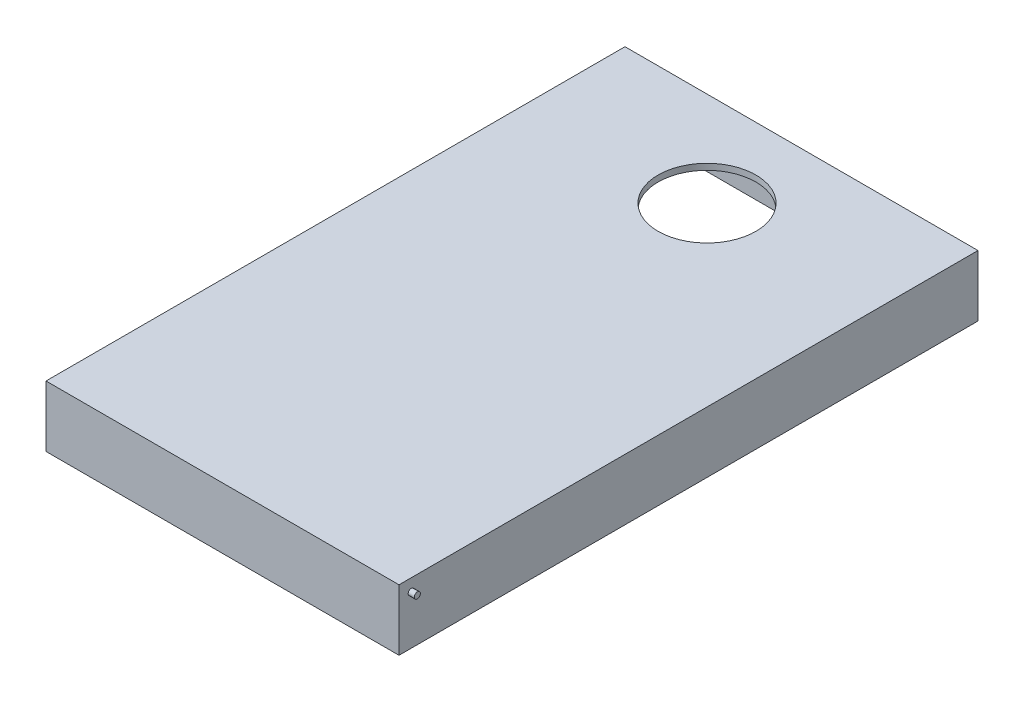
SolidWorks part; units mm, degrees
ref_plane "Front Plane" through (0, 0, 0) normal (0, 0, 1) x (1, 0, 0)
ref_plane "Top Plane" through (0, 0, 0) normal (0, 1, 0) x (1, 0, 0)
ref_plane "Right Plane" through (0, 0, 0) normal (1, 0, 0) x (0, 0, -1)
sketch "Sketch2" plane through (0, 0, 0) normal (0, 1, 0) x (1, 0, 0)
  line L0 (28.9, 24.0111) -> (28.9, 118.8111)
  line L1 (28.9, 24.0111) -> (-28.9, 24.0111)
  line L2 (28.9, 118.8111) -> (-28.9, 118.8111)
  line L3 (-28.9, 24.0111) -> (-28.9, 118.8111)
  point P1 (0, 0)
  dimension "D1" = 57.8
  dimension "D2" = 94.8
extrude "Boss-Extrude1" add sketch "Sketch2" against normal blind 10
shell "Shell1" thickness 1
sketch "Sketch3" plane through (0, 0, 0) normal (0, 1, 0) x (1, 0, 0)
  circle A0 centre (0, 103.3407) radius 8
extrude "Cut-Extrude1" cut sketch "Sketch3" against normal through all
sketch "Sketch4" plane through (28.9, 0, 0) normal (1, 0, 0) x (0, 0, -1)
  line L0 (24.0111, 0) -> (118.8111, 0) construction
  line L1 (24.0111, -10) -> (24.0111, 0) construction
  circle A0 centre (26.0111, -2) radius 0.5
  dimension "D1" = 1
  dimension "D2" = 2
  dimension "D3" = 2
extrude "Boss-Extrude2" add sketch "Sketch4" along normal blind 1
mirror "Mirror1" about plane through (0, 0, 0) normal (1, 0, 0) of "Boss-Extrude2"
